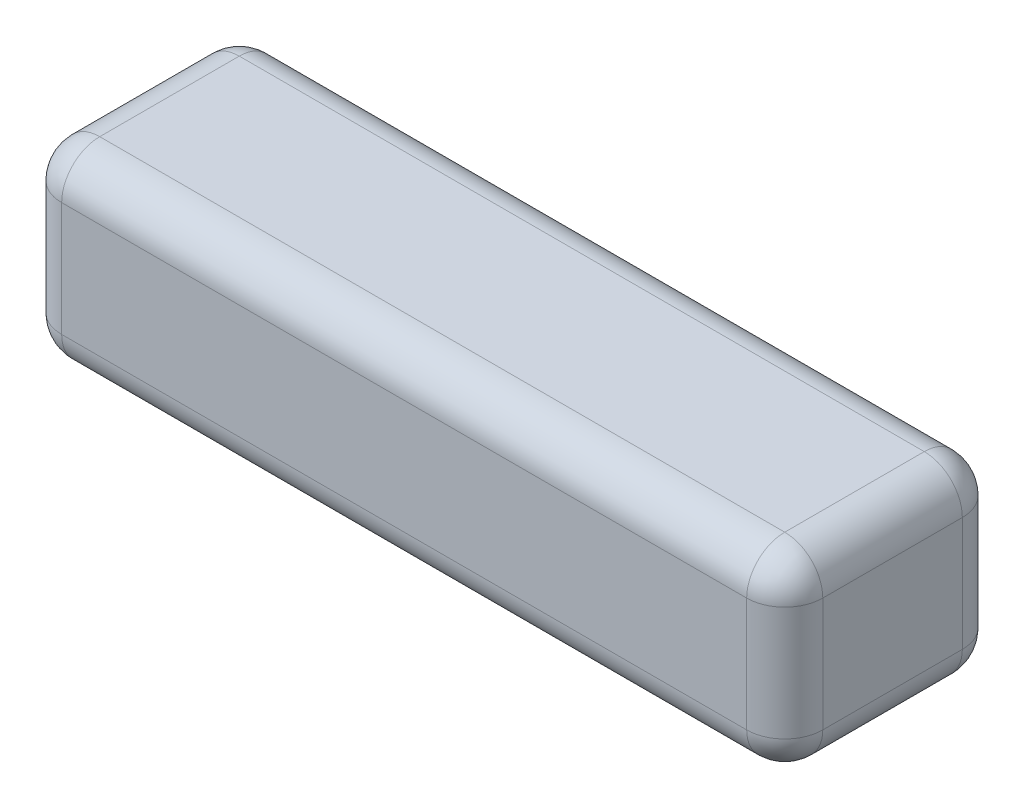
SolidWorks part; units mm, degrees
ref_plane "Front Plane" through (0, 0, 0) normal (0, 0, 1) x (1, 0, 0)
ref_plane "Top Plane" through (0, 0, 0) normal (0, 1, 0) x (1, 0, 0)
ref_plane "Right Plane" through (0, 0, 0) normal (1, 0, 0) x (0, 0, -1)
sketch "Sketch1" plane through (0, 0, 0) normal (0, 1, 0) x (1, 0, 0)
  line L1 (-30, 8.5) -> (30, 8.5)
  line L2 (-30, 8.5) -> (-30, -8.5)
  line L3 (-30, -8.5) -> (30, -8.5)
  line L4 (30, 8.5) -> (30, -8.5)
  line L5 (-30, 8.5) -> (30, -8.5) construction
  line L6 (-30, -8.5) -> (30, 8.5) construction
  point P0 (0, 0)
  dimension "D1" = 60
  dimension "D2" = 17
extrude "Boss-Extrude1" add sketch "Sketch1" along normal blind 15
fillet "Fillet2" radius 3 12 edges at (-30, 15, 0) (30, 15, 0) (30, 0, 0) (0, 0, -8.5) (-30, 0, 0) (0, 0, 8.5) (0, 15, -8.5) (0, 15, 8.5) (30, 7.5, -8.5) (30, 7.5, 8.5) (-30, 7.5, 8.5) (-30, 7.5, -8.5)
